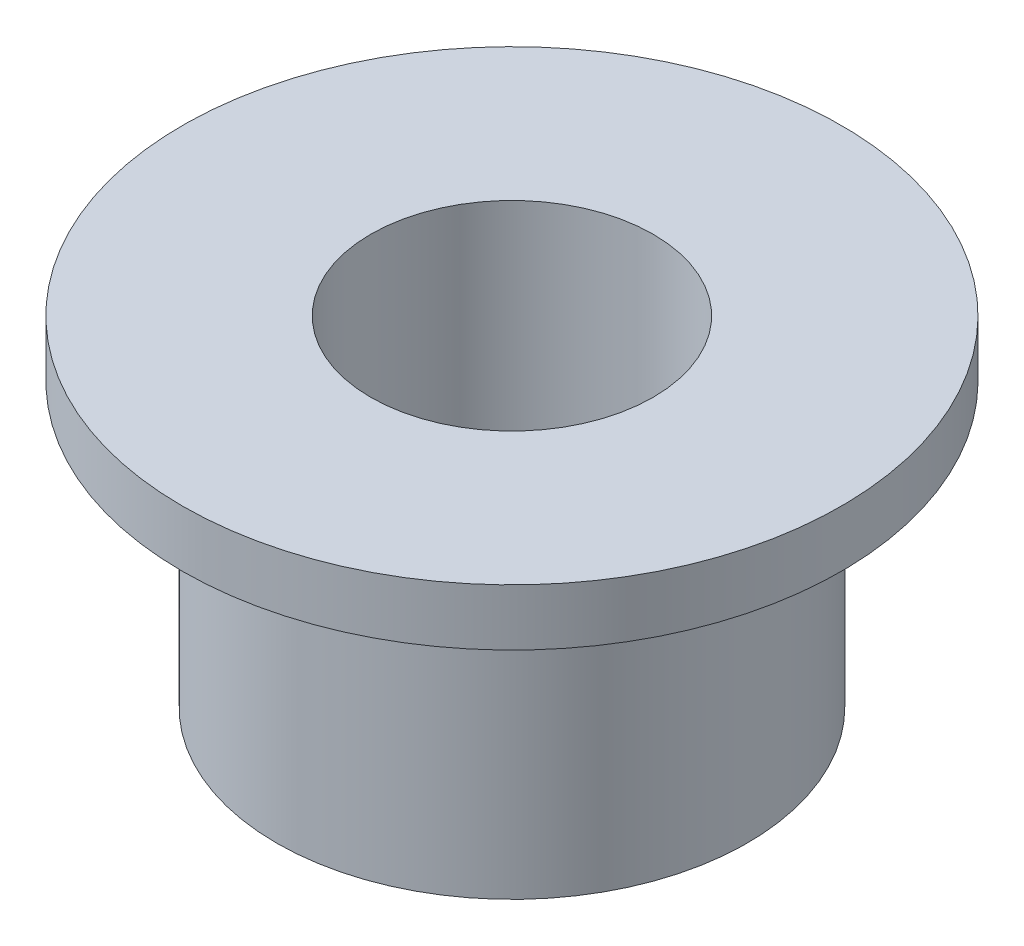
SolidWorks part; units mm, degrees
other "标注1"
sketch "草图4" plane through (3.5, 3.6, 3.5) normal (0.4, 0.515, 0.7581) x (0.8844, 0, -0.4667)
ref_plane "前视基准面" through (0, 0, 0) normal (0, 0, 1) x (1, 0, 0)
ref_plane "上视基准面" through (0, 0, 0) normal (0, 1, 0) x (1, 0, 0)
ref_plane "右视基准面" through (0, 0, 0) normal (1, 0, 0) x (0, 0, -1)
sketch "草图2" plane through (0, 0, 0) normal (0, 1, 0) x (1, 0, 0)
  circle A0 centre (0, 0) radius 1.5
  circle A1 centre (0, 0) radius 2.5
  dimension "D1" = 3
  dimension "D2" = 5
extrude "凸台-拉伸1" add sketch "草图2" along normal blind 3
sketch "草图3" plane through (0, 3, 0) normal (0, 1, 0) x (1, 0, 0)
  circle A0 centre (0, 0) radius 1.5
  circle A1 centre (0, 0) radius 3.5
  dimension "D1" = 7
extrude "凸台-拉伸2" add sketch "草图3" along normal blind 0.6
